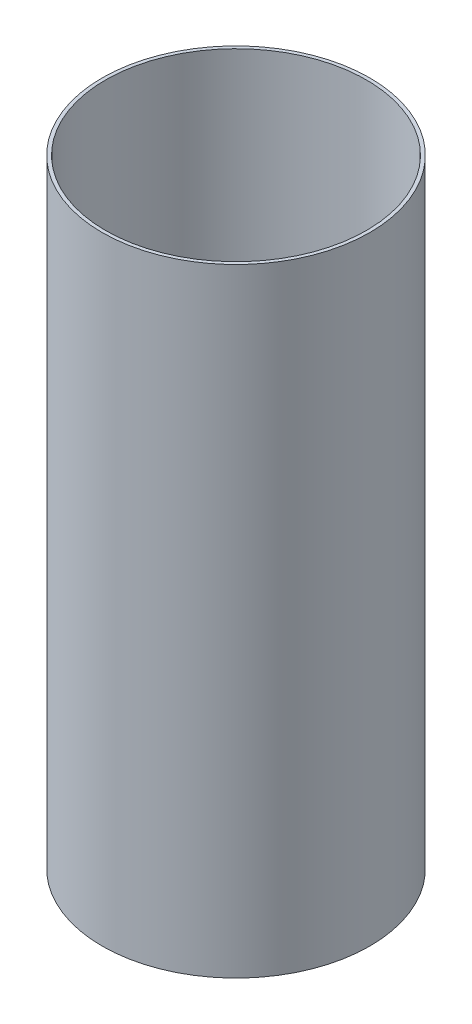
SolidWorks part; units mm, degrees
material "A-Glass Fiber"
ref_plane "Front Plane" through (0, 0, 0) normal (0, 0, 1) x (1, 0, 0)
ref_plane "Top Plane" through (0, 0, 0) normal (0, 1, 0) x (1, 0, 0)
ref_plane "Right Plane" through (0, 0, 0) normal (1, 0, 0) x (0, 0, -1)
sketch "Sketch1" plane through (0, 0, 0) normal (0, 1, 0) x (1, 0, 0)
  circle A0 centre (0, 0) radius 49.53
  circle A1 centre (0, 0) radius 48.26
  dimension "D1" = 99.06
  dimension "D2" = 96.52
extrude "Boss-Extrude1" add sketch "Sketch1" along normal blind 228.6 contours A1 | A0
equation "\"Length\"= 9"
equation "\"D1@Boss-Extrude1\"=\"Length\""
